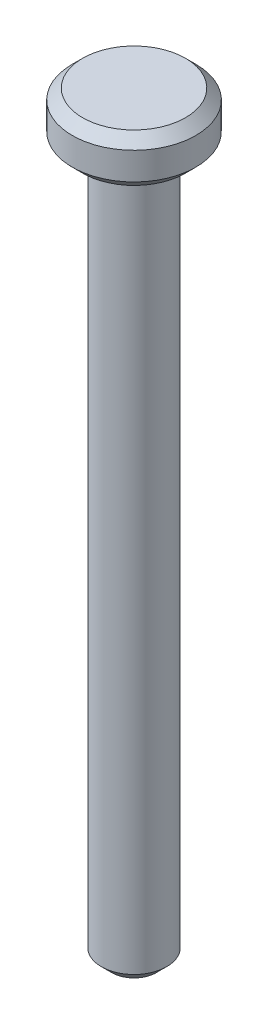
SolidWorks part; units mm, degrees
ref_plane "Front Plane" through (0, 0, 0) normal (0, 0, 1) x (1, 0, 0)
ref_plane "Top Plane" through (0, 0, 0) normal (0, 1, 0) x (1, 0, 0)
ref_plane "Right Plane" through (0, 0, 0) normal (1, 0, 0) x (0, 0, -1)
sketch "Sketch1" plane through (0, 0, 0) normal (1, 0, 0) x (0, 0, -1)
  line L0 (0, 0) -> (0, 37.1542) construction
  line L1 (0, 0) -> (3.2625, 0)
  line L2 (4.7625, 1.5) -> (4.7625, 101.5)
  line L3 (0, 0) -> (0, 110)
  line L4 (0, 110) -> (7.5, 110)
  line L5 (9, 108.5) -> (9, 104.5)
  line L6 (7.5, 103) -> (6.2625, 103)
  line L7 (7.5, 110) -> (9, 108.5)
  line L8 (9, 104.5) -> (7.5, 103)
  line L9 (4.7625, 101.5) -> (6.2625, 103)
  line L10 (3.2625, 0) -> (4.7625, 1.5)
  point P3 (9, 110)
  point P4 (4.7625, 0)
  point P5 (4.7625, 103)
  point P8 (9, 103)
  point P14 (0, 0)
  dimension "D1" = 9
revolve "Revolve1" add sketch "Sketch1" angle 360 about L0
